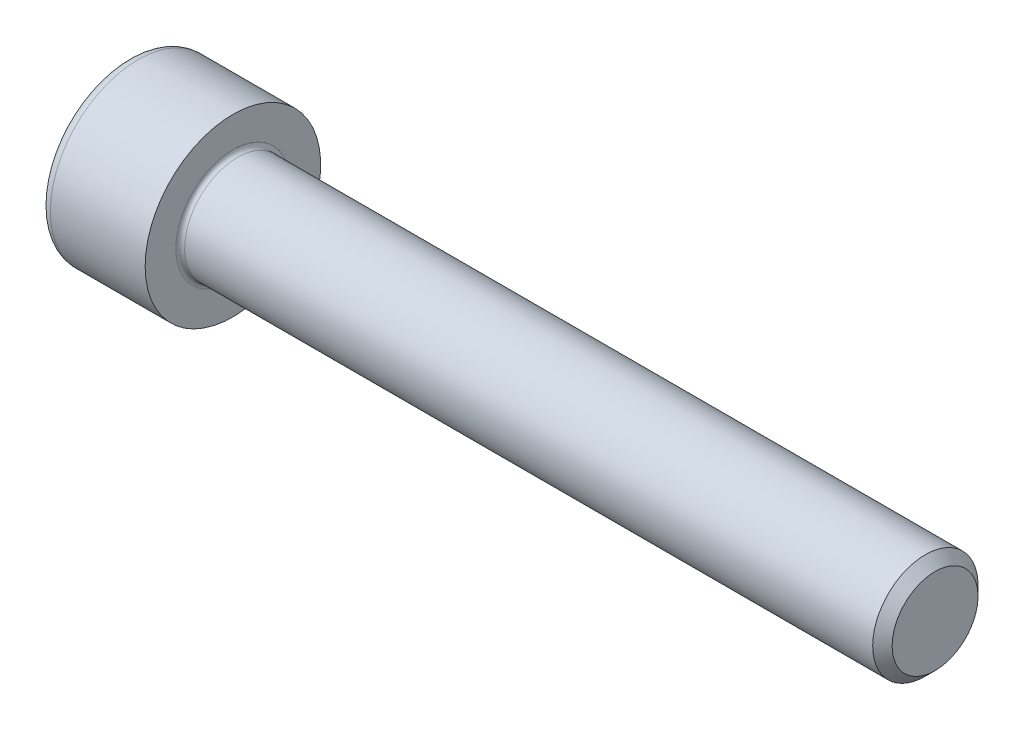
SolidWorks part; units mm, degrees
ref_plane "Plane1" through (0, 0, 0) normal (0, 0, 1) x (1, 0, 0)
ref_plane "Plane2" through (0, 0, 0) normal (0, 1, 0) x (1, 0, 0)
ref_plane "Plane3" through (0, 0, 0) normal (1, 0, 0) x (0, 0, -1)
sketch "BodySke" plane through (0, 0, 0) normal (0, 0, 1) x (1, 0, 0)
  line L0 (0, 0) -> (0, 5)
  line L1 (0, 5) -> (6, 5)
  line L2 (6, 5) -> (6, 3)
  line L3 (6, 3) -> (45.4455, 3)
  line L4 (46, 2.4455) -> (46, 0)
  line L5 (46, 0) -> (0, 0)
  line L6 (-31.75, 0) -> (127, 0) construction
  line L8 (46, 2.4455) -> (45.4455, 3)
  line L10 (46, -2.4455) -> (45.4455, -3) construction
  line L11 (7, 9.525) -> (7, 3.175) construction
  line L12 (22, 9.525) -> (22, 3.175) construction
  line L13 (-14, 9.525) -> (-14, 3.175) construction
  dimension "Diameter" = 6
  dimension "Head_ht" = 6
  dimension "Length" = 40
  dimension "Body_ch_ang" = 45
  dimension "Head_dia" = 10
  dimension "Minor_dia" = 4.891
  dimension "Advance" = 1
  dimension "Thread_nom" = 24
  dimension "Thread_length" = 60
revolve "Base-Revolve" add sketch "BodySke"
cosmetic thread "ThreadCosmetic" [suppressed]
fillet "Fillet1" radius 0.25 1 edges at (6, 0, 3)
fillet "Fillet2" radius 0.6 1 edges at (0, 0, 5)
sketch "Sketch2" plane through (0, 0, 0) normal (0, 0, 1) x (1, 0, 0)
  line L0 (0, 2.51) -> (3, 2.51)
  line L1 (3, 2.51) -> (4.4491, 0)
  line L2 (-31.75, 0) -> (127, 0) construction
  line L3 (4.4491, 0) -> (0, 0)
  line L4 (0, 0) -> (0, 2.51)
  line L6 (0, 0) -> (47.625, 0) construction
  dimension "D1" = 2.51
  dimension "D2" = 60
  dimension "Depth" = 3
revolve "Hex-PreBroach" cut sketch "Sketch2" angle 360 about L6
sketch "Sketch3" plane through (0, 0, 0) normal (-1, 0, 0) x (0, 0.5, 0.866)
  line L0 (1.4491, 2.51) -> (-1.4491, 2.51)
  line L1 (-1.4491, 2.51) -> (-2.8983, 0)
  line L2 (1.4491, 2.51) -> (2.8983, 0)
  line L3 (1.4491, -2.51) -> (2.8983, 0)
  line L4 (1.4491, -2.51) -> (-1.4491, -2.51)
  line L5 (-1.4491, -2.51) -> (-2.8983, 0)
  dimension "D1" = 2.51
  dimension "D2" = 2.51
  dimension "Hex_size" = 5.02
extrude "Hex" cut sketch "Sketch3" against normal blind 3
sketch "ThdSchSke" plane through (0, 0, 0) normal (0, 0, 1) x (1, 0, 0)
  line L0 (22, -2.4455) -> (21.6117, -3)
  line L1 (22, -2.4455) -> (22.3883, -3)
  line L2 (22.3883, -3) -> (22.3883, -3.75)
  line L3 (-3.175, 0) -> (5.1513, 0) construction
  line L4 (0, 4.4) -> (0, -4.4) construction
  line L5 (22.3883, -3.75) -> (21.6117, -3.75)
  line L6 (21.6117, -3.75) -> (21.6117, -3)
  dimension "Thread_minor" = 4.891
  dimension "Diameter" = 6
  dimension "Start" = 22
  dimension "SideAngle" = 55
  dimension "VeeAngle" = 70
  dimension "Overcut" = 7.5
revolve "ThreadSchematic" [suppressed] cut sketch "ThdSchSke" angle 360 about L3
pattern_linear "ThdSchPat" [suppressed]
equation "\"D2@Sketch3\" = \"Hex_size@Sketch3\" / 2"
equation "\"D1@Sketch3\" = \"Hex_size@Sketch3\" / 2"
equation "\"D1@Sketch2\" = \"Hex_size@Sketch3\" / 2"
equation "\"Thread_minor@ThreadCosmetic\"  =  \"Minor_dia@BodySke\""
equation "\"Depth@Sketch2\" =  \"Key_eng@Hex\""
equation "\"Thread_length@ThreadCosmetic\" = ((sgn( (\"Length@BodySke\" - \"Advance@BodySke\" * 3.0) - \"Thread_nom@BodySke\" )-1)*( (\"Length@BodySke\" - \"Advance@BodySke\" * 3.0) - \"Thread_nom@BodySke\" ))/-2+ \"Thread_nom@BodySke\""
equation "\"Thread_minor@ThdSchSke\" = \"Minor_dia@BodySke\""
equation "\"Diameter@ThdSchSke\" = \"Diameter@BodySke\""
equation "\"Overcut@ThdSchSke\" = \"Diameter@BodySke\" * 1.25"
equation "\"Start@ThdSchSke\" = \"Head_ht@BodySke\" + \"Length@BodySke\" - \"Thread_length@ThreadCosmetic\"  '---Non-countersunk---"
equation "\"Num_threads@ThdSchPat\" = int( \"Thread_length@ThreadCosmetic\" / \"Advance@BodySke\" + 0.999 )  + 1"
equation "\"Advance@ThdSchPat\" = \"Thread_length@ThreadCosmetic\" /  (\"Num_threads@ThdSchPat\" - 1) 'relax it"
equation "\"Num_threads@ThdSchPat\" = \"Num_threads@ThdSchPat\" - sgn( \"Num_threads@ThdSchPat\" - 1) '---chamfered tips only---"
